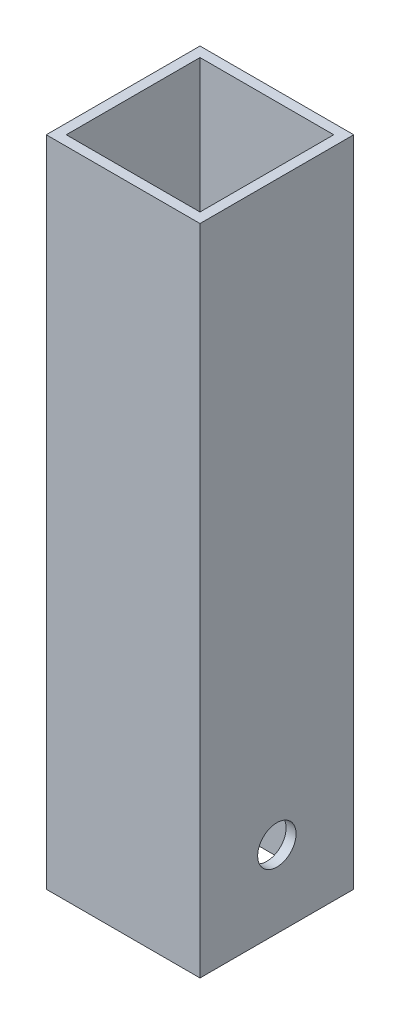
SolidWorks part; units mm, degrees
material "6061 Alloy"
ref_plane "Front Plane" through (0, 0, 0) normal (0, 0, 1) x (1, 0, 0)
ref_plane "Top Plane" through (0, 0, 0) normal (0, 1, 0) x (1, 0, 0)
ref_plane "Right Plane" through (0, 0, 0) normal (1, 0, 0) x (0, 0, -1)
sketch "Sketch1" plane through (0, 0, 0) normal (0, 1, 0) x (1, 0, 0)
  line L1 (0, 0) -> (25.4, 0)
  line L2 (0, 0) -> (0, -25.4)
  line L3 (0, -25.4) -> (25.4, -25.4)
  line L4 (25.4, 0) -> (25.4, -25.4)
extrude "Boss-Extrude1" add sketch "Sketch1" along normal blind 107.95
sketch "Sketch2" plane through (0, 107.95, 0) normal (0, 1, 0) x (1, 0, 0)
  line L0 (0, 0) -> (0, -25.4) construction
  line L1 (1.651, -1.651) -> (23.749, -1.651)
  line L2 (1.651, -1.651) -> (1.651, -23.749)
  line L3 (1.651, -23.749) -> (23.749, -23.749)
  line L4 (23.749, -1.651) -> (23.749, -23.749)
  line L5 (25.4, 0) -> (0, 0) construction
  line L6 (25.4, -25.4) -> (25.4, 0) construction
  line L7 (0, -25.4) -> (25.4, -25.4) construction
  dimension "D1" = 1.651
  dimension "D2" = 1.651
  dimension "D3" = 1.651
  dimension "D4" = 1.651
extrude "Cut-Extrude1" cut sketch "Sketch2" against normal through all
sketch "Sketch3" plane through (0, 0, 0) normal (-1, 0, 0) x (0, 0, 1)
  line L0 (0, 0) -> (25.4, 0) construction
  line L1 (0, 107.95) -> (0, 0) construction
  circle A0 centre (12.7, 12.7) radius 3.175
  dimension "D1" = 6.35
  dimension "D2" = 12.7
  dimension "D3" = 12.7
extrude "Cut-Extrude2" cut sketch "Sketch3" against normal through all
